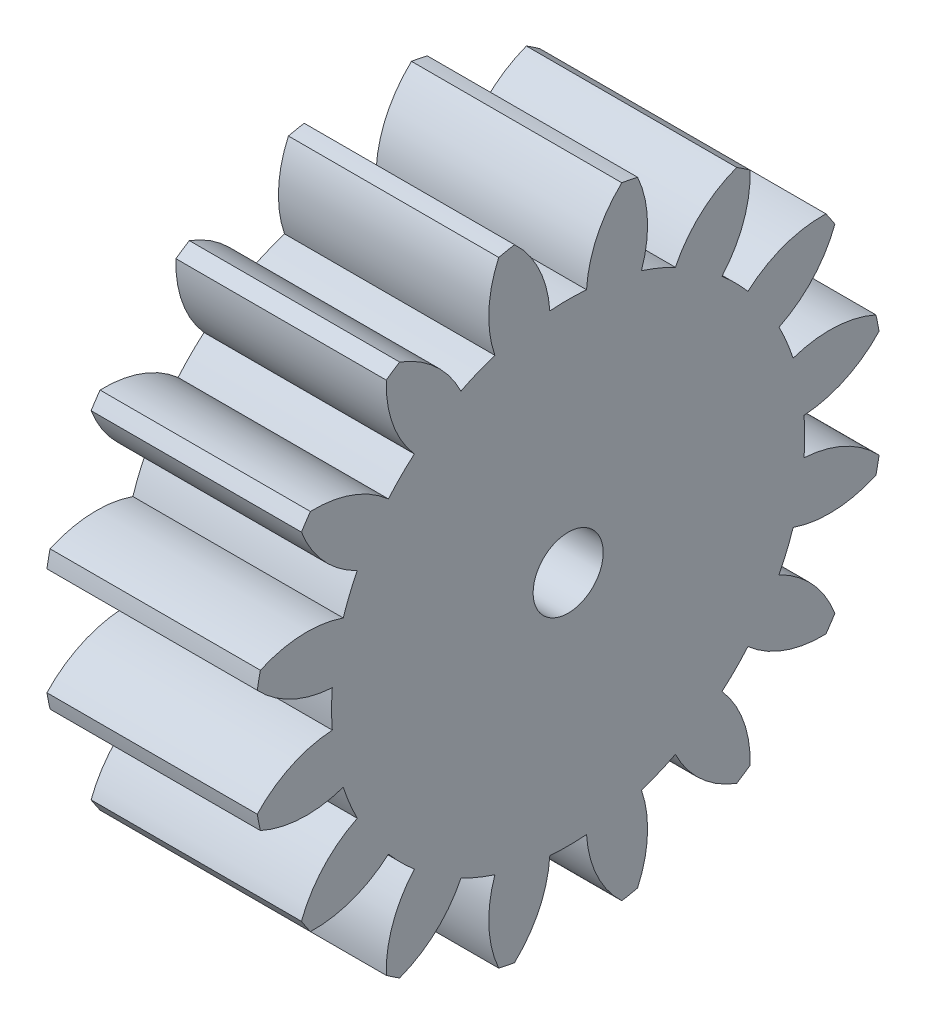
SolidWorks part; units mm, degrees
ref_plane "Plane1" through (0, 0, 0) normal (0, 0, 1) x (1, 0, 0)
ref_plane "Plane2" through (0, 0, 0) normal (0, 1, 0) x (1, 0, 0)
ref_plane "Plane3" through (0, 0, 0) normal (1, 0, 0) x (0, 0, -1)
sketch "HoldingSke" plane through (0, 0, 0) normal (0, 1, 0) x (1, 0, 0)
  line L0 (0, 0) -> (0.9613, -0.2756)
  line L1 (-15, 0) -> (100, 0) construction
  line L2 (0, 0) -> (-2.1039, 2.3779)
  line L3 (0, 0) -> (-11.863, 4.5341)
  line L4 (0, 0) -> (8.3015, 2.3804)
  line L5 (0, 0) -> (-46.8476, -17.4728)
  line L6 (0, 0) -> (-4.9738, -3.3558)
  line L7 (-2.1039, 2.3779) -> (8.6586, 51.2059)
  line L8 (-76.2, 54.61) -> (-75.9, 54.61)
  line L9 (-71.009, 38.7566) -> (-53.1078, 45.2721)
  line L10 (-76.2, 71.12) -> (104.1128, 71.12)
  line L11 (0, 0) -> (-6, 0)
  line L12 (-76.2, 101.6) -> (-76.162, 101.6)
  line L13 (24.9733, 27.94) -> (52.9518, 28.4284)
  line L14 (24.9733, 27.94) -> (24.9743, 27.94)
  line L15 (24.9733, 27.94) -> (100.4006, 29.5858)
  line L16 (-63.627, -1) -> (-12.827, -1)
  circle A0 centre (0, 0) radius 1
  circle A1 centre (0, 0) radius 6.749
  circle A2 centre (0, 0) radius 37.5
  circle A3 centre (0, 0) radius 1
  dimension "MHD" = 13.498
  dimension "Hub_dia" = 75
  dimension "Bore" = 2
  dimension "MBD" = 2
  dimension "Num_teeth" = 16
  dimension "Pitch" = 1
  dimension "Overall_len" = 50
  dimension "Show_teeth" = 16
  dimension "Thickness" = 6
  dimension "OAL" = 50.0001
  dimension "T_dim" = 0.3
  dimension "Ap" = 20
  dimension "H" = 19.05
  dimension "Pitch_radius" = 180.3128
  dimension "Width" = 6
  dimension "Backlash" = 0.038
  dimension "Addendum_fac" = 1
  dimension "Dedendum_fac" = 1.25
  dimension "Clearance_fac" = 0.25
  dimension "Dedendum_add" = 0.001
  dimension "Module" = 1
sketch "BasProSke" plane through (0, 0, 0) normal (0, 1, 0) x (1, 0, 0)
  line L0 (-10, 0) -> (60, 0) construction
  line L1 (0, 0) -> (0, 9)
  line L2 (0, 0) -> (6, 0)
  line L3 (6, 0) -> (6, 9)
  line L4 (6, 9) -> (0, 9)
  dimension "Thickness" = 6
  dimension "Diameter" = 18
revolve "Base-Revolve" add sketch "BasProSke" angle 360 about L0
sketch "TooCutSke" plane through (0, 0, 0) normal (1, 0, 0) x (0, 0, -1)
  line L1 (0, 0) -> (0, 107) construction
  line L2 (0, 0) -> (-0.8506, 7.9547) construction
  line L3 (0, 0) -> (-3.1089, 15.6293) construction
  line L4 (-0.8506, 7.9547) -> (-1.5544, 7.8146) construction
  arc A0 (0.5238, 6.7286) -> (-0.5238, 6.7286) centre (0, 0) ccw
  arc A1 (1.5534, 8.8907) -> (-1.5534, 8.8907) centre (0, 0) ccw
  circle A2 centre (0, 0) radius 8 construction
  circle A3 centre (0, 0) radius 7.5175 construction
  arc A4 (-0.5238, 6.7286) -> (-1.5534, 8.8907) centre (-3.7179, 6.5338) ccw
  arc A5 (1.5534, 8.8907) -> (0.5238, 6.7286) centre (3.7179, 6.5338) ccw
  dimension "Root_dia" = 13.498
  dimension "Overcut_dia" = 18.0508
  dimension "Pitch_dia" = 16
  dimension "Base_dia" = 15.0351
  dimension "Flank_rad" = 3.2
  dimension "Half_ang" = 11.25
  dimension "Half_CT" = 0.7176
extrude "ToothCut" cut sketch "TooCutSke" along normal through all
fillet "Breaks" [suppressed] radius 0.02
fillet "RootFillets" [suppressed] radius 0.251
pattern_circular "TeethCuts" count 16 every 22.5 about axis through (-10, 0, 0) along (1, 0, 0) of "ToothCut", "RootFillets", "Breaks"
sketch "HubNeaOneSke" plane through (0, 0, 0) normal (-1, 0, 0) x (0, 0, 1)
  circle A0 centre (0, 0) radius 6.749
  dimension "Diameter" = 13.498
extrude "HubNearOne" [suppressed] add sketch "HubNeaOneSke" along normal blind 44.0001
sketch "HubNeaBotSke" plane through (0, 0, 0) normal (-1, 0, 0) x (0, 0, 1)
  circle A0 centre (0, 0) radius 6.749
  dimension "Diameter" = 13.498
extrude "HubNearBoth" [suppressed] add sketch "HubNeaBotSke" along normal blind 22
ref_plane "FarPln" through (6, 0, 0) normal (1, 0, 0) x (0, 0, -1)
sketch "HubFarSke" plane through (6, 0, 0) normal (1, 0, 0) x (0, 0, -1)
  circle A0 centre (0, 0) radius 6.749
  dimension "Diameter" = 13.498
extrude "HubFar" [suppressed] add sketch "HubFarSke" along normal blind 22
sketch "BorSke" plane through (0, 0, 0) normal (1, 0, 0) x (0, 0, -1)
  circle A0 centre (0, 0) radius 1
  dimension "Diameter" = 2
extrude "Bore" cut sketch "BorSke" along normal mid plane 100.0001
sketch "KeySke" plane through (0, 0, 0) normal (1, 0, 0) x (0, 0, -1)
  line L0 (-0.4, 0) -> (-0.4, 1.3)
  line L1 (-0.4, 1.3) -> (0.4, 1.3)
  line L2 (0.4, 1.3) -> (0.4, 0)
  line L3 (0, 0) -> (0, 34) construction
  line L4 (-0.4, 0) -> (0.4, 0)
  dimension "Offset" = 1.3
  dimension "Width" = 0.8
extrude "Keyway" [suppressed] cut sketch "KeySke" along normal mid plane 100.0001
pattern_circular "Keyway2" [suppressed] count 2 every 90 about axis through (-10, 0, 0) along (1, 0, 0)
equation "' \"Module@HoldingSke\" = 6.35"
equation "' \"Num_teeth@HoldingSke\" = 12"
equation "' \"Ap@HoldingSke\" =  20"
equation "' \"Ap@HoldingSke\" = 20"
equation "' \"Width@HoldingSke\" = 0.5 * 25.4"
equation "' \"Hub_dia@HoldingSke\"= 1 * 25.4"
equation "' \"Hub_dia@HoldingSke\" = 1 * 25.4"
equation "' \"Overall_len@HoldingSke\" = 1.0 * 25.4"
equation "' \"Bore@HoldingSke\" = 0.75 * 25.4"
equation "' \"T_dim@HoldingSke\" = 0.1 * 25.4"
equation "' \"Width@KeySke\" = 0.25 * 25.4"
equation "' \"Show_teeth@HoldingSke\" = 13"
equation "' \"Backlash@HoldingSke\" = 0.009 * 25.4"
equation "' \"Addendum_fac@HoldingSke\" = 1.0"
equation "' \"Dedendum_fac@HoldingSke\" = 1.25"
equation "' \"Dedendum_add@HoldingSke\" = 0.00005 * 25.4"
equation "' \"Clearance_fac@HoldingSke\" = 0.25"
equation "\"Pitch@HoldingSke\" = 1 / \"Module@HoldingSke\""
equation "\"Overcut_dia@TooCutSke\" = (\"Num_teeth@HoldingSke\" + 2 * \"Addendum_fac@HoldingSke\") / \"Pitch@HoldingSke\" + 0.002 * 25.4"
equation "\"Pitch_dia@TooCutSke\" = \"Num_teeth@HoldingSke\" / \"Pitch@HoldingSke\""
equation "\"Base_dia@TooCutSke\" = \"Num_teeth@HoldingSke\" / \"Pitch@HoldingSke\" * cos((\"Ap@HoldingSke\"  * 3.14159265 / 180))"
equation "\"Root_dia@TooCutSke\" = (\"Num_teeth@HoldingSke\" + 2) / \"Pitch@HoldingSke\" - 2 * (\"Addendum_fac@HoldingSke\" + \"Dedendum_fac@HoldingSke\") / \"Pitch@HoldingSke\" - \"Dedendum_add@HoldingSke\" * 2"
equation "\"Half_ang@TooCutSke\" = 180 / \"Num_teeth@HoldingSke\""
equation "\"Half_CT@TooCutSke\" = \"Num_teeth@HoldingSke\" / \"Pitch@HoldingSke\" * sin((3.14159265 / 2 / \"Num_teeth@HoldingSke\")) / 2 - 7 * \"Backlash@HoldingSke\" / 4"
equation "\"Flank_rad@TooCutSke\" = \"Num_teeth@HoldingSke\" / \"Pitch@HoldingSke\" / 5"
equation "\"Radius@RootFillets\" = \"Clearance_fac@HoldingSke\" / \"Pitch@HoldingSke\" + \"Dedendum_add@HoldingSke\""
equation "\"Break_rad@Breaks\" = 0.02 / \"Pitch@HoldingSke\""
equation "\"Thickness@HoldingSke\" = \"Width@HoldingSke\""
equation "\"OAL@HoldingSke\" = \"Thickness@HoldingSke\""
equation "\"MHD@HoldingSke\" = (\"Num_teeth@HoldingSke\" + 2) / \"Pitch@HoldingSke\" - 2 * (\"Addendum_fac@HoldingSke\" + \"Dedendum_fac@HoldingSke\")  / \"Pitch@HoldingSke\" - \"Dedendum_add@HoldingSke\" * 2"
equation "\"MBD@HoldingSke\" = (\"Num_teeth@HoldingSke\" + 2) / \"Pitch@HoldingSke\" - 2 * (\"Addendum_fac@HoldingSke\" + \"Dedendum_fac@HoldingSke\")  / \"Pitch@HoldingSke\" - \"Dedendum_add@HoldingSke\" * 2 - 0.002 * 25.4"
equation "\"MHD@HoldingSke\" = ((sgn( \"MHD@HoldingSke\" - \"Hub_dia@HoldingSke\" )-1)*( \"MHD@HoldingSke\" - \"Hub_dia@HoldingSke\" ))/-2+ \"Hub_dia@HoldingSke\""
equation "\"MBD@HoldingSke\" = ((sgn( \"MBD@HoldingSke\" - \"Bore@HoldingSke\" )-1)*( \"MBD@HoldingSke\" - \"Bore@HoldingSke\" ))/-2+ \"Bore@HoldingSke\""
equation "\"OAL@HoldingSke\" = ((sgn( \"OAL@HoldingSke\" - \"Overall_len@HoldingSke\" )+1)*( \"OAL@HoldingSke\" - \"Overall_len@HoldingSke\" ))/2 + \"Overall_len@HoldingSke\" + 0.000002 * 25.4"
equation "\"Num_teeth@TeethCuts\" = int( \"Show_teeth@HoldingSke\" ) + 1"
equation "\"Num_teeth@TeethCuts\" = ((sgn( \"Num_teeth@TeethCuts\" - \"Num_teeth@HoldingSke\" )-1)*( \"Num_teeth@TeethCuts\" - \"Num_teeth@HoldingSke\" ))/-2+ \"Num_teeth@HoldingSke\""
equation "\"Num_teeth@TeethCuts\" = ((sgn( \"Num_teeth@TeethCuts\" - 2.0)+1)*( \"Num_teeth@TeethCuts\" - 2.0))/2 +2.0"
equation "\"Angle@TeethCuts\" = 360.0 / \"Num_teeth@HoldingSke\""
equation "\"Diameter@BasProSke\" = (\"Num_teeth@HoldingSke\" + 2 * \"Addendum_fac@HoldingSke\") / \"Pitch@HoldingSke\""
equation "\"Thickness@BasProSke\"  = \"Thickness@HoldingSke\""
equation "' \"Fillet_rad@BasProSke\" =  \"Thickness@HoldingSke\" * 0.05"
equation "' \"Fillet_rad@BasProSke\" = \"Thickness@HoldingSke\" * 0.05"
equation "\"MHD@HoldingSke\" = ((sgn( \"MHD@HoldingSke\" - \"Root_dia@TooCutSke\" )-1)*( \"MHD@HoldingSke\" - \"Root_dia@TooCutSke\" ))/-2+ \"Root_dia@TooCutSke\""
equation "\"Diameter@HubNeaOneSke\" = \"MHD@HoldingSke\""
equation "\"Length@HubNearOne\" = \"OAL@HoldingSke\" - \"Thickness@BasProSke\""
equation "\"Diameter@HubNeaBotSke\" = \"MHD@HoldingSke\""
equation "\"Length@HubNearBoth\" = ( \"OAL@HoldingSke\" - \"Thickness@BasProSke\" ) / 2.0"
equation "\"Thickness@FarPln\" = \"Thickness@BasProSke\""
equation "\"Diameter@HubFarSke\" = \"MHD@HoldingSke\""
equation "\"Length@HubFar\" = ( \"OAL@HoldingSke\" - \"Thickness@BasProSke\" ) / 2.0"
equation "\"D1@Bore\" = \"OAL@HoldingSke\" * 2.0"
equation "\"D1@Keyway\" = \"OAL@HoldingSke\" * 2.0"
equation "\"Offset@KeySke\" = \"T_dim@HoldingSke\" + \"MBD@HoldingSke\" / 2.0"
